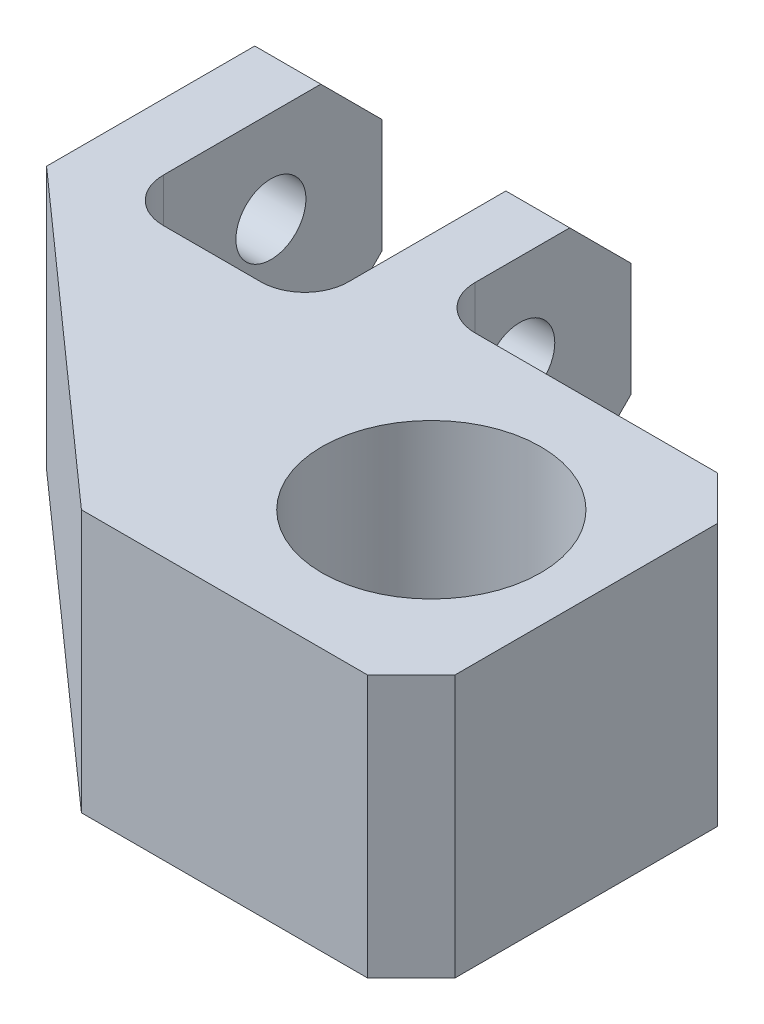
SolidWorks part; units mm, degrees
ref_plane "Спереди" through (0, 0, 0) normal (0, 0, 1) x (1, 0, 0)
ref_plane "Сверху" through (0, 0, 0) normal (0, 1, 0) x (1, 0, 0)
ref_plane "Справа" through (0, 0, 0) normal (1, 0, 0) x (0, 0, -1)
sketch "Эскиз1" plane through (0, 0, 0) normal (0, 1, 0) x (1, 0, 0)
  line L0 (0, 0) -> (74.0729, 0) construction
  line L1 (-20, 20) -> (17.7037, 20)
  line L2 (-20, 20) -> (-20, -20)
  line L3 (-20, -20) -> (17.7037, -20)
  line L5 (0, 0) -> (0, 55.7233) construction
  line L11 (17.7037, 20) -> (17.7037, -20)
  circle A0 centre (0, 0) radius 12.5
  dimension "D4" = 20
extrude "Вытянуть1" add sketch "Эскиз1" along normal blind 30
sketch "Эскиз8" plane through (0, 0, 0) normal (0, -1, 0) x (1, 0, 0)
  line L0 (-20, 20) -> (-56, -12.0137)
  line L2 (-20, 20) -> (-20, -42.8153)
  line L3 (-20, -42.8153) -> (-56, -42.8153)
  line L4 (-56, -12.0137) -> (-56, -42.8153)
extrude "Вытянуть3" add sketch "Эскиз8" against normal blind 30
sketch "Эскиз9" plane through (0, 0, -42.8153) normal (0, 0, -1) x (-1, 0, 0)
  line L1 (27.2971, 30.4304) -> (48.4486, 30.4304)
  line L2 (27.2971, 30.4304) -> (27.2971, -3.1301)
  line L3 (27.2971, -3.1301) -> (48.4486, -3.1301)
  line L4 (48.4486, 30.4304) -> (48.4486, -3.1301)
extrude "Вырез-Вытянуть5" cut sketch "Эскиз9" against normal blind 30
fillet "Скругление4" radius 5 2 edges at (-48.4486, 15, -12.8153) (-27.2971, 15, -12.8153)
chamfer "Фаска4" distance 7 angle 45 2 edges at (-52.2243, 30, -42.8153) (-23.6485, 30, -42.8153)
fillet "Скругление5" radius 5 1 edges
sketch "Эскиз10" plane through (-56, 0, 0) normal (-1, 0, 0) x (0, 0, 1)
  circle A0 centre (-30.1099, 19.4845) radius 4
extrude "Вырез-Вытянуть6" cut sketch "Эскиз10" against normal through all
chamfer "Фаска6" distance 10 angle 45 2 edges at (-23.6485, 0, -42.8153) (-52.2243, 0, -42.8153)
chamfer "Фаска7" distance 5 angle 45 2 edges at (17.7037, 15, -20) (17.7037, 15, 20)
